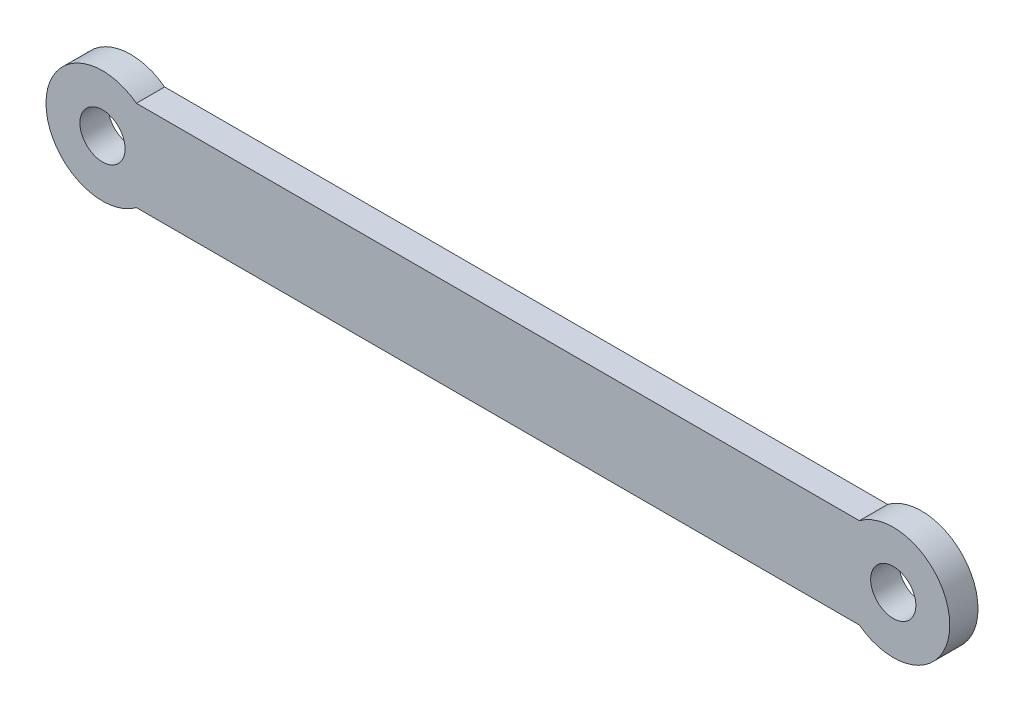
SolidWorks part; units mm, degrees
ref_plane "Piano frontale" through (0, 0, 0) normal (0, 0, 1) x (1, 0, 0)
ref_plane "Piano superiore" through (0, 0, 0) normal (0, 1, 0) x (1, 0, 0)
ref_plane "Piano destro" through (0, 0, 0) normal (1, 0, 0) x (0, 0, -1)
sketch "Schizzo1" plane through (0, 0, 0) normal (0, 0, 1) x (1, 0, 0)
  line L0 (0, 0) -> (4, 0) construction
  line L1 (6, -8) -> (134, -8)
  line L2 (6, 8) -> (134, 8)
  line L3 (0, 8) -> (140, 8) construction
  line L4 (0, -8) -> (140, -8) construction
  line L5 (136, 0) -> (140, 0) construction
  line L6 (0, 0) -> (140, 0) construction
  circle A0 centre (0, 0) radius 4
  circle A1 centre (140, 0) radius 4
  arc A2 (6, 8) -> (6, -8) centre (0, 0) ccw
  arc A3 (134, -8) -> (134, 8) centre (140, 0) ccw
  dimension "D1" = 8
  dimension "D2" = 8
  dimension "D4" = 20
  dimension "D5" = 20
  dimension "D3" = 140
  dimension "D6" = 8
  dimension "D7" = 8
extrude "Estrusione-Estrusione1" add sketch "Schizzo1" along normal blind 5
